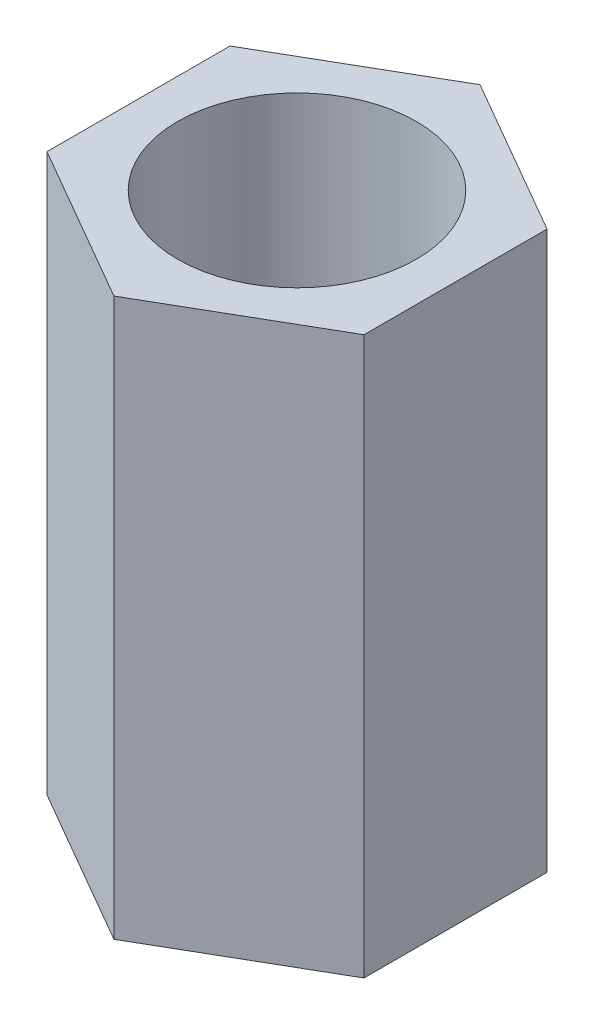
SolidWorks part; units mm, degrees
material "黄铜"
ref_plane "前视基准面" through (0, 0, 0) normal (0, 0, 1) x (1, 0, 0)
ref_plane "上视基准面" through (0, 0, 0) normal (0, 1, 0) x (1, 0, 0)
ref_plane "右视基准面" through (0, 0, 0) normal (1, 0, 0) x (0, 0, -1)
other "Configuration Table"
sketch "草图1" plane through (0, 0, 0) normal (0, 1, 0) x (1, 0, 0)
  line L0 (0, 0) -> (0, 3.0947) construction
  line L1 (1.9919, 1.15) -> (0, 2.3)
  line L2 (0, 2.3) -> (-1.9919, 1.15)
  line L3 (-1.9919, 1.15) -> (-1.9919, -1.15)
  line L4 (-1.9919, -1.15) -> (0, -2.3)
  line L5 (0, -2.3) -> (1.9919, -1.15)
  line L6 (1.9919, -1.15) -> (1.9919, 1.15)
  circle A0 centre (0, 0) radius 1.5
  circle A1 centre (0, 0) radius 1.9919 construction
  dimension "D1" = 3
  dimension "D2" = 4.6
extrude "凸台-拉伸1" add sketch "草图1" along normal blind 7
